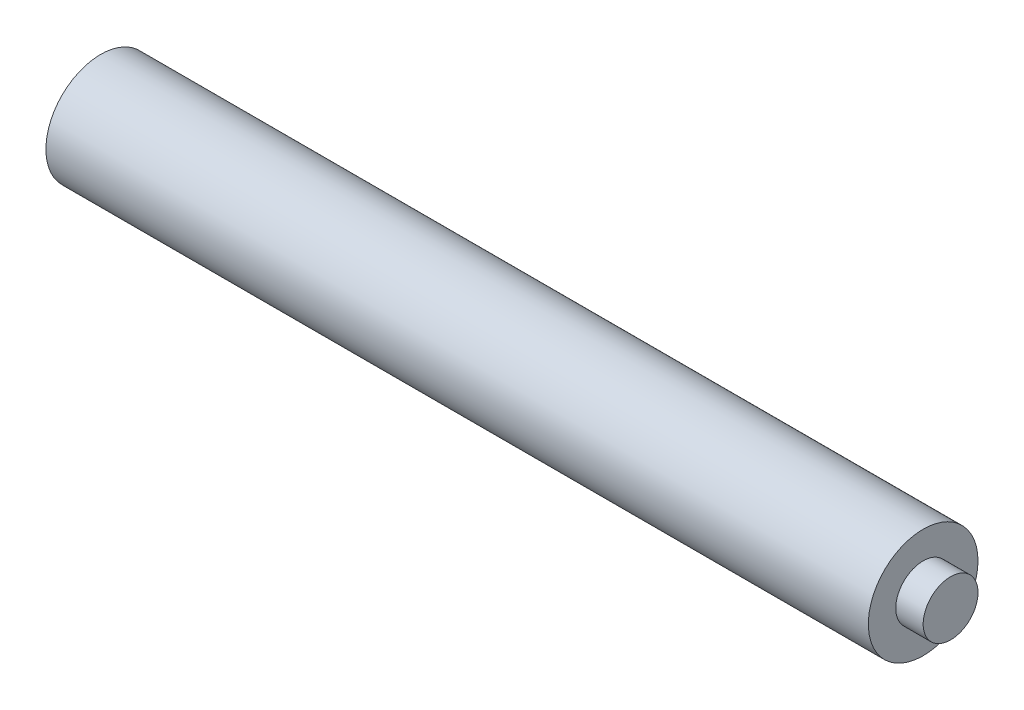
SolidWorks part; units mm, degrees
ref_plane "Front Plane" through (0, 0, 0) normal (0, 0, 1) x (1, 0, 0)
ref_plane "Top Plane" through (0, 0, 0) normal (0, 1, 0) x (1, 0, 0)
ref_plane "Right Plane" through (0, 0, 0) normal (1, 0, 0) x (0, 0, -1)
sketch "Sketch1" plane through (0, 0, 0) normal (1, 0, 0) x (0, 0, -1)
  circle A0 centre (0, 0) radius 4
  dimension "D1" = 8
extrude "Boss-Extrude1" add sketch "Sketch1" along normal mid plane 60
sketch "Sketch2" plane through (30, 0, 0) normal (1, 0, 0) x (0, 0, -1)
  circle A0 centre (0, 0) radius 2
  dimension "D1" = 4
extrude "Boss-Extrude2" add sketch "Sketch2" along normal blind 2
